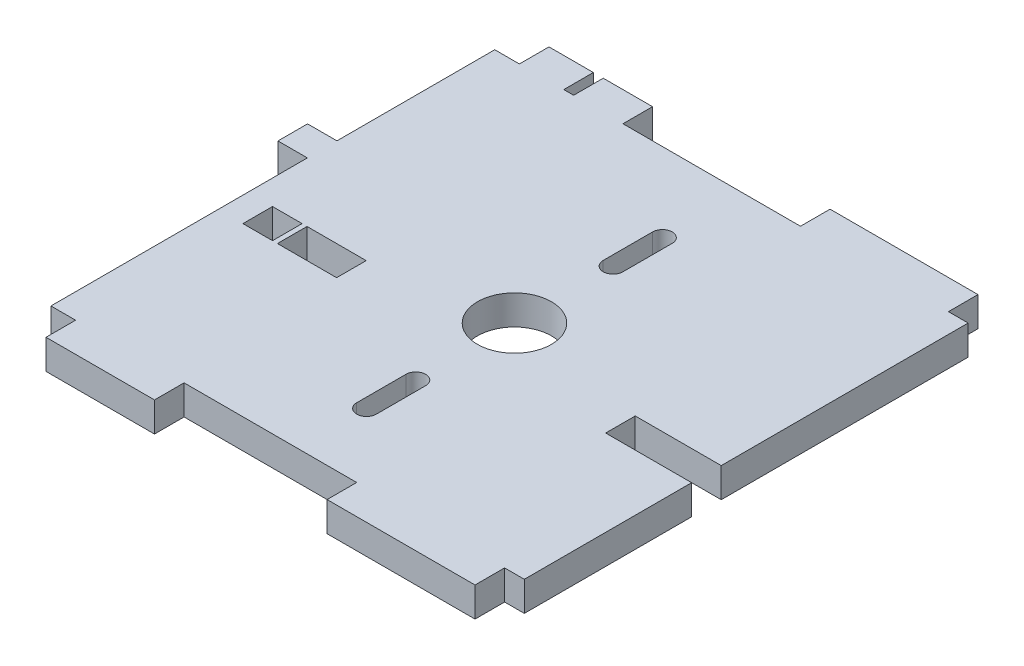
SolidWorks part; units mm, degrees
ref_plane "Alzado" through (0, 0, 0) normal (0, 0, 1) x (1, 0, 0)
ref_plane "Planta" through (0, 0, 0) normal (0, 1, 0) x (1, 0, 0)
ref_plane "Vista lateral" through (0, 0, 0) normal (1, 0, 0) x (0, 0, -1)
sketch "Croquis1" plane through (0, 0, 0) normal (0, 0, 1) x (1, 0, 0)
  line L0 (41643.6148, 57982.9088) -> (41643.6148, 57977.9088)
  line L1 (41641.6148, 57982.9088) -> (41641.6148, 57977.9088)
  line L2 (41643.6148, 58007.9088) -> (41643.6148, 58002.9088)
  line L3 (41641.6148, 58007.9088) -> (41641.6148, 58002.9088)
  line L34 (41630.6148, 58015.9088) -> (41648.6148, 58015.9088)
  line L48 (41620.1148, 57967.9088) -> (41631.1152, 57967.9088)
  line L49 (41648.6152, 57967.9088) -> (41663.6152, 57967.9088)
  line L50 (41631.1152, 57967.9088) -> (41631.1152, 57970.9088)
  line L51 (41631.1152, 57970.9088) -> (41648.6152, 57970.9088)
  line L52 (41648.6152, 57967.9088) -> (41648.6152, 57970.9088)
  line L55 (41620.1148, 57967.9088) -> (41620.1148, 57970.9088)
  line L56 (41663.6152, 57967.9088) -> (41663.6152, 57970.9088)
  line L57 (41620.1148, 58015.9088) -> (41620.1148, 58018.9088)
  line L58 (41620.1148, 58018.9088) -> (41624.6148, 58018.9088)
  line L59 (41624.6148, 58015.9088) -> (41624.6148, 58018.9088)
  line L60 (41625.6148, 58015.9088) -> (41625.6148, 58018.9088)
  line L61 (41630.6148, 58015.9088) -> (41630.6148, 58018.9088)
  line L62 (41624.6148, 58015.9088) -> (41625.6148, 58015.9088)
  line L63 (41625.6148, 58018.9088) -> (41630.6148, 58018.9088)
  line L64 (41648.6148, 58015.9088) -> (41648.6148, 58018.9088)
  line L65 (41663.6148, 58015.9088) -> (41663.6148, 58018.9088)
  line L66 (41648.6148, 58018.9088) -> (41663.6148, 58018.9088)
  line L67 (41663.6148, 58015.9088) -> (41665.6148, 58015.9088)
  line L69 (41663.6152, 57970.9088) -> (41665.6148, 57970.9088)
  line L78 (41620.1148, 58015.9088) -> (41617.6148, 58015.9088)
  line L79 (41617.6148, 58015.9088) -> (41617.6148, 57999.9088)
  line L80 (41620.1148, 57970.9088) -> (41617.6148, 57970.9088)
  line L81 (41617.6148, 57996.9088) -> (41617.6148, 57970.9088)
  line L84 (41617.6148, 57999.9088) -> (41614.6335, 57999.9088)
  line L87 (41614.6335, 57999.9088) -> (41614.6335, 57996.9088)
  line L113 (41665.6148, 57970.9088) -> (41665.6148, 57987.8734)
  line L118 (41614.6335, 57996.9088) -> (41617.6148, 57996.9088)
  line L120 (41656.8967, 57990.8734) -> (41656.8967, 57987.8734)
  line L121 (41656.8967, 57987.8734) -> (41665.6148, 57987.8734)
  line L122 (41665.6148, 57990.8734) -> (41656.8967, 57990.8734)
  line L128 (41629.6166, 57987.8734) -> (41623.6166, 57987.8734)
  line L129 (41620.1166, 57990.8734) -> (41620.1166, 57987.8734)
  line L131 (41623.1166, 57990.8734) -> (41623.1166, 57987.8734)
  line L132 (41623.6166, 57990.8734) -> (41623.6166, 57987.8734)
  line L133 (41629.6166, 57990.8734) -> (41629.6166, 57987.8734)
  line L134 (41629.6166, 57990.8734) -> (41623.6166, 57990.8734)
  line L135 (41665.6148, 57990.8734) -> (41665.6148, 58015.9088)
  line L136 (41623.1166, 57987.8734) -> (41620.1166, 57987.8734)
  line L137 (41623.1166, 57990.8734) -> (41620.1166, 57990.8734)
  arc A1 (41643.6148, 58007.9088) -> (41641.6148, 58007.9088) centre (41642.6148, 58007.9088) ccw
  arc A2 (41641.6148, 58002.9088) -> (41643.6148, 58002.9088) centre (41642.6148, 58002.9088) ccw
  arc A3 (41643.6148, 57982.9088) -> (41641.6148, 57982.9088) centre (41642.6148, 57982.9088) ccw
  arc A4 (41641.6148, 57977.9088) -> (41643.6148, 57977.9088) centre (41642.6148, 57977.9088) ccw
  circle A5 centre (41642.6148, 57992.9088) radius 3.75
extrude "Saliente-Extruir1" add sketch "Croquis1" along normal blind 3
move or copy body "Sólido-Mover/Copiar1" bodies to move or copy 101 copy no rotation origin (0, 57992.4088, 1.5) rotation axis (-1, 0, 0) rotation angle 90
